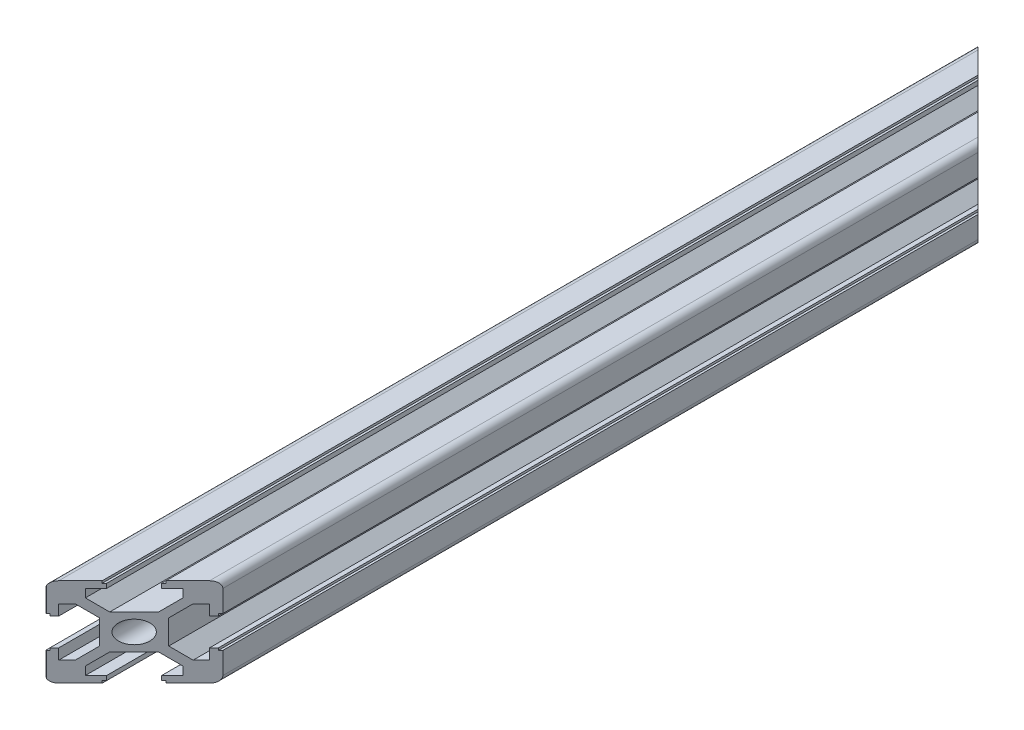
SolidWorks part; units mm, degrees
ref_plane "Plane1" through (0, 0, 0) normal (0, 0, 1) x (1, 0, 0)
ref_plane "Plane2" through (0, 0, 0) normal (0, 1, 0) x (1, 0, 0)
ref_plane "Plane3" through (0, 0, 0) normal (1, 0, 0) x (0, 0, -1)
sketch "Sketch1" plane through (0, 0, 0) normal (0, 0, 1) x (1, 0, 0)
  line L0 (-3.6, 10) -> (-3.6, 9.5)
  line L1 (-3.6, 9.5) -> (-3.1, 9.5)
  line L2 (-3.1, 9.5) -> (-3.1, 8.5)
  line L3 (-3.1, 8.5) -> (-5.5, 8.5)
  line L4 (-8.5, -10) -> (-3.6, -10)
  line L5 (-10, -8.5) -> (-10, -3.6)
  line L6 (8.5, 10) -> (3.6, 10)
  line L7 (10, 8.5) -> (10, 3.6)
  line L8 (0, 14.8756) -> (0, 0) construction
  line L9 (0, 0) -> (14.1675, 0) construction
  line L10 (-5.5, 8.5) -> (-5.5, 6.65)
  line L11 (-5.5, 6.65) -> (-2.75, 3.9)
  line L12 (-2.75, 3.9) -> (2.75, 3.9)
  line L13 (5.5, 6.65) -> (2.75, 3.9)
  line L14 (5.5, 8.5) -> (5.5, 6.65)
  line L15 (3.1, 8.5) -> (5.5, 8.5)
  line L16 (3.1, 9.5) -> (3.1, 8.5)
  line L17 (3.6, 9.5) -> (3.1, 9.5)
  line L18 (3.6, 10) -> (3.6, 9.5)
  line L19 (-3.6, 10) -> (-8.5, 10)
  line L20 (10, 3.6) -> (9.5, 3.6)
  line L21 (9.5, 3.6) -> (9.5, 3.1)
  line L22 (9.5, 3.1) -> (8.5, 3.1)
  line L23 (8.5, 3.1) -> (8.5, 5.5)
  line L24 (8.5, 5.5) -> (6.65, 5.5)
  line L25 (6.65, 5.5) -> (3.9, 2.75)
  line L26 (3.9, 2.75) -> (3.9, -2.75)
  line L27 (6.65, -5.5) -> (3.9, -2.75)
  line L28 (8.5, -5.5) -> (6.65, -5.5)
  line L29 (8.5, -3.1) -> (8.5, -5.5)
  line L30 (9.5, -3.1) -> (8.5, -3.1)
  line L31 (9.5, -3.6) -> (9.5, -3.1)
  line L32 (10, -3.6) -> (9.5, -3.6)
  line L33 (3.6, -10) -> (3.6, -9.5)
  line L34 (3.6, -9.5) -> (3.1, -9.5)
  line L35 (3.1, -9.5) -> (3.1, -8.5)
  line L36 (3.1, -8.5) -> (5.5, -8.5)
  line L37 (5.5, -8.5) -> (5.5, -6.65)
  line L38 (5.5, -6.65) -> (2.75, -3.9)
  line L39 (2.75, -3.9) -> (-2.75, -3.9)
  line L40 (-5.5, -6.65) -> (-2.75, -3.9)
  line L41 (-5.5, -8.5) -> (-5.5, -6.65)
  line L42 (-3.1, -8.5) -> (-5.5, -8.5)
  line L43 (-3.1, -9.5) -> (-3.1, -8.5)
  line L44 (-3.6, -9.5) -> (-3.1, -9.5)
  line L45 (-3.6, -10) -> (-3.6, -9.5)
  line L46 (-10, -3.6) -> (-9.5, -3.6)
  line L47 (-9.5, -3.6) -> (-9.5, -3.1)
  line L48 (-9.5, -3.1) -> (-8.5, -3.1)
  line L49 (-8.5, -3.1) -> (-8.5, -5.5)
  line L50 (-8.5, -5.5) -> (-6.65, -5.5)
  line L51 (-6.65, -5.5) -> (-3.9, -2.75)
  line L52 (-3.9, -2.75) -> (-3.9, 2.75)
  line L53 (-6.65, 5.5) -> (-3.9, 2.75)
  line L54 (-8.5, 5.5) -> (-6.65, 5.5)
  line L55 (-8.5, 3.1) -> (-8.5, 5.5)
  line L56 (-9.5, 3.1) -> (-8.5, 3.1)
  line L57 (-9.5, 3.6) -> (-9.5, 3.1)
  line L58 (-10, 3.6) -> (-9.5, 3.6)
  line L59 (3.6, -10) -> (8.5, -10)
  line L60 (-10, 3.6) -> (-10, 8.5)
  line L61 (10, -3.6) -> (10, -8.5)
  circle A0 centre (0, 0) radius 2.5
  arc A1 (-10, 8.5) -> (-8.5, 10) centre (-8.5, 8.5) cw
  arc A2 (10, 8.5) -> (8.5, 10) centre (8.5, 8.5) ccw
  arc A3 (-8.5, -10) -> (-10, -8.5) centre (-8.5, -8.5) cw
  arc A4 (8.5, -10) -> (10, -8.5) centre (8.5, -8.5) ccw
  point P0 (-10, 0)
  point P1 (10, 0)
  point P2 (0, 10)
  point P3 (0, -10)
  point P4 (0, 0)
  point P5 (-10, -10)
  point P6 (10, -10)
  point P7 (10, 10)
  point P8 (-10, 10)
  point P36 (-10, 10)
  point P39 (10, 10)
extrude "凸台-拉伸1" add sketch "Sketch1" along normal blind 210
sketch "草图1" plane through (0, 10, 0) normal (0, 1, 0) x (1, 0, 0)
  line L0 (-9.8687, -210) -> (10.1313, -210)
  line L1 (10.1313, -210) -> (10.1313, -190)
  line L2 (10.1313, -190) -> (-9.8687, -210)
  line L3 (-9.9109, 0) -> (10.0891, 0)
  line L4 (10.0891, 0) -> (10.0891, -20)
  line L5 (10.0891, -20) -> (-9.9109, 0)
  dimension "D1" = 20
  dimension "D2" = 20
  dimension "D3" = 20
  dimension "D4" = 20
extrude "切除-拉伸1" cut sketch "草图1" against normal through all
